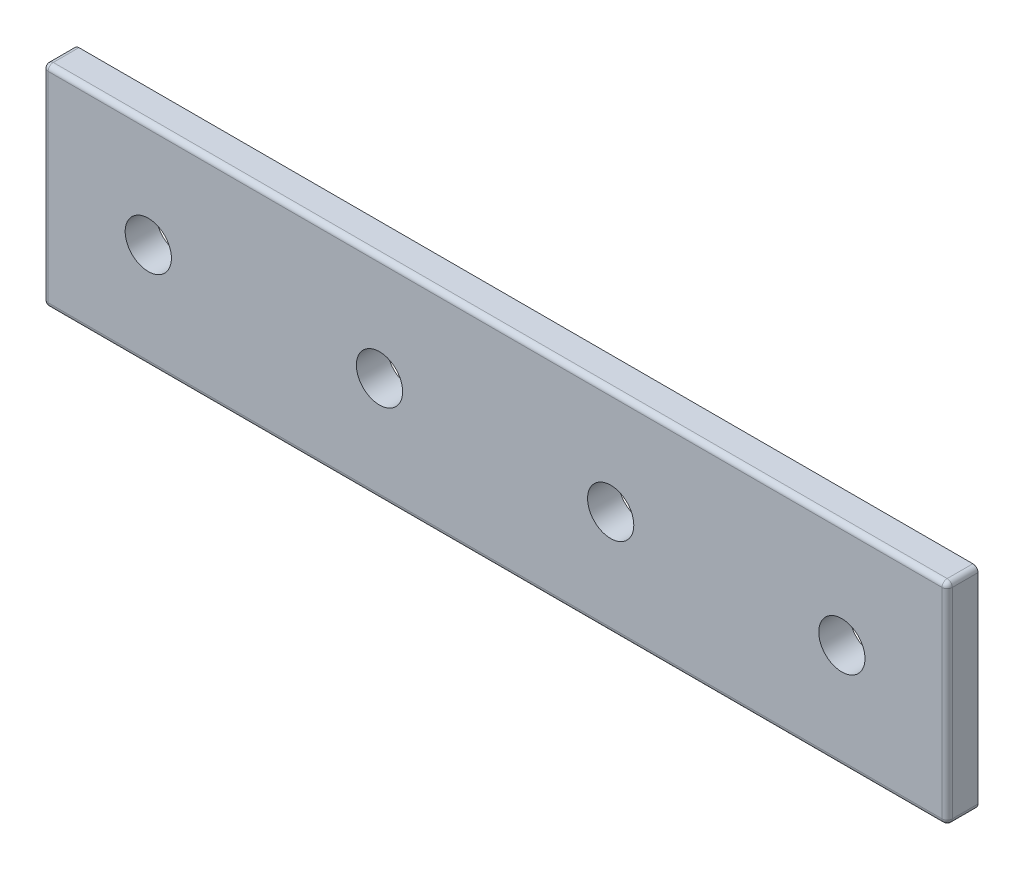
SolidWorks part; units mm, degrees
ref_plane "Front Plane" through (0, 0, 0) normal (0, 0, 1) x (1, 0, 0)
ref_plane "Top Plane" through (0, 0, 0) normal (0, 1, 0) x (1, 0, 0)
ref_plane "Right Plane" through (0, 0, 0) normal (1, 0, 0) x (0, 0, -1)
sketch "Sketch1" plane through (0, 0, 0) normal (0, 0, 1) x (1, 0, 0)
  line L0 (0, 0) -> (0, 41)
  line L1 (20.5, 20.5) -> (65.5, 20.5) construction
  line L2 (65.5, 20.5) -> (110.5, 20.5) construction
  line L3 (110.5, 20.5) -> (155.5, 20.5) construction
  line L4 (176, 41) -> (0, 41)
  line L5 (176, 0) -> (0, 0)
  line L7 (176, 41) -> (176, 0)
  circle A0 centre (20.5, 20.5) radius 4.5
  circle A1 centre (65.5, 20.5) radius 4.5
  circle A2 centre (110.5, 20.5) radius 4.5
  circle A3 centre (155.5, 20.5) radius 4.5
  dimension "D1" = 45
  dimension "E" = 9
  dimension "D2" = 20.5
  dimension "C" = 41
  dimension "D3" = 20.5
  dimension "B" = 176
extrude "Boss-Extrude1" add sketch "Sketch1" along normal mid plane 6
fillet "Fillet1" radius 1 8 edges at (0, 0, 0) (0, 20.5, 3) (88, 0, 3) (176, 20.5, 3) (176, 0, 0) (176, 41, 0) (88, 41, 3) (0, 41, 0)
